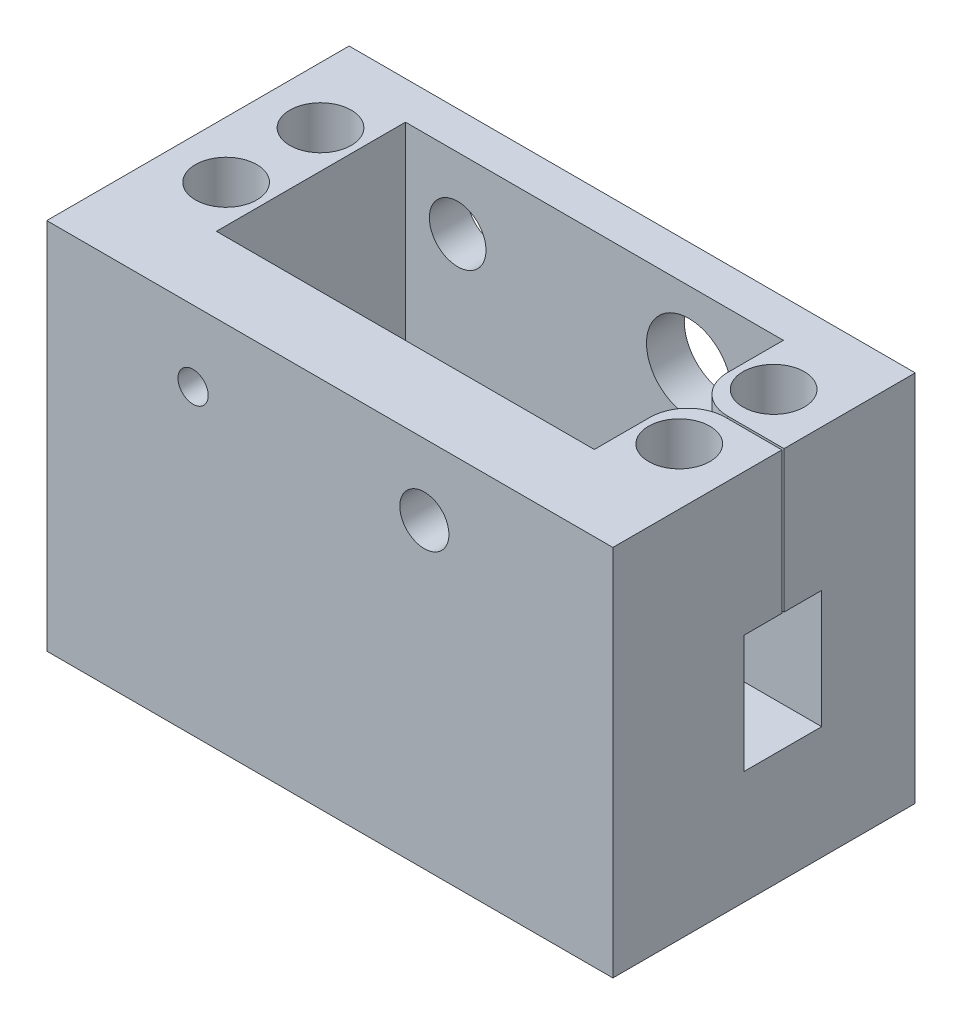
SolidWorks part; units mm, degrees
ref_plane "Front Plane" through (0, 0, 0) normal (0, 0, 1) x (1, 0, 0)
ref_plane "Top Plane" through (0, 0, 0) normal (0, 1, 0) x (1, 0, 0)
ref_plane "Right Plane" through (0, 0, 0) normal (1, 0, 0) x (0, 0, -1)
sketch "Sketch1" plane through (0, 0, 0) normal (0, 1, 0) x (1, 0, 0)
  line L0 (20.015, 0) -> (27.985, 0)
  line L1 (27.985, -14.015) -> (-27.985, -14.015)
  line L2 (27.985, -14.015) -> (27.985, 14.015)
  line L3 (27.985, 14.015) -> (-27.985, 14.015)
  line L4 (-27.985, -14.015) -> (-27.985, 14.015)
  line L5 (27.985, -14.015) -> (-27.985, 14.015) construction
  line L6 (27.985, 14.015) -> (-27.985, -14.015) construction
  line L7 (20.015, -10.015) -> (-20.015, -10.015)
  line L8 (20.015, -10.015) -> (20.015, 10.015)
  line L9 (20.015, 10.015) -> (-20.015, 10.015)
  line L10 (-20.015, -10.015) -> (-20.015, 10.015)
  line L11 (20.015, -10.015) -> (-20.015, 10.015) construction
  line L12 (20.015, 10.015) -> (-20.015, -10.015) construction
  line L13 (24, -5) -> (-24, -5) construction
  line L14 (24, -5) -> (24, 5) construction
  line L15 (24, 5) -> (-24, 5) construction
  line L16 (-24, -5) -> (-24, 5) construction
  line L17 (24, -5) -> (-24, 5) construction
  line L18 (24, 5) -> (-24, -5) construction
  line L19 (-27.985, -14.015) -> (-27.985, -18.015)
  line L20 (-27.985, -18.015) -> (27.985, -18.015)
  line L21 (27.985, -18.015) -> (27.985, -14.015)
  line L22 (27.985, 14.015) -> (29.985, 14.015)
  line L23 (29.985, 14.015) -> (29.985, 0.115)
  line L24 (29.985, 0.115) -> (24, 0.115)
  line L25 (27.985, -14.015) -> (29.985, -14.015)
  line L26 (29.985, -14.015) -> (29.985, -0.115)
  line L27 (29.985, -0.115) -> (24, -0.115)
  line L28 (27.985, -18.015) -> (29.985, -18.015)
  line L29 (29.985, -18.015) -> (29.985, -14.015)
  line L30 (-27.985, 14.015) -> (-29.985, 14.015)
  line L31 (-29.985, 14.015) -> (-29.985, -18.015)
  line L32 (-29.985, -18.015) -> (-27.985, -18.015)
  circle A1 centre (24, 5) radius 3.25
  circle A2 centre (24, -5) radius 3.25
  circle A3 centre (-24, -5) radius 3.25
  circle A4 centre (-24, 5) radius 3.25
  arc A5 (20.015, 4.1) -> (27.985, 4.1) centre (24, 4.1) ccw
  arc A6 (20.015, -4.1) -> (27.985, -4.1) centre (24, -4.1) cw
  point P0 (0, 0)
  point P6 (0, 0)
  point P11 (0, 0)
  dimension "D1" = 6.5
  dimension "D7" = 4.1
  dimension "D8" = 4.1
  dimension "D2" = 48
  dimension "D3" = 4
  dimension "D4" = 40.03
  dimension "D5" = 20.03
  dimension "D6" = 10
  dimension "D9" = 4
  dimension "D10" = 2
  dimension "D11" = 2
extrude "Boss-Extrude1" add sketch "Sketch1" along normal mid plane 15 contours A6 L8 L7 L10 L9 A5 L2 L3 L4 L1 A4 A3 A2 A1 | L20 L21 L1 L19 | L24 L23 L22 L2 | L26 L27 L2 L25 | L27 A6 L2 | A5 L24 L2 | L28 L29 L25 L21 | L31 L32 L19 L4 L30
sketch "Sketch2" plane through (0, -7.5, 0) normal (0, -1, 0) x (1, 0, 0)
  circle A0 centre (24, -5) radius 3.25 construction
  circle A1 centre (24, 5) radius 3.25 construction
  circle A2 centre (-24, -5) radius 3.25 construction
  circle A3 centre (-24, 5) radius 3.25 construction
  circle A4 centre (24, -5) radius 3.25
  circle A5 centre (24, 5) radius 3.25
  circle A6 centre (-24, -5) radius 3.25
  circle A7 centre (-24, 5) radius 3.25
extrude "Boss-Extrude2" add sketch "Sketch2" against normal offset from surface (5 mm away) 10 up to face at (10.4535, 7.5, 0.5714)
sketch "Sketch3" plane through (0, 0, 18.015) normal (0, 0, 1) x (1, 0, 0)
  line L0 (10.015, 0) -> (-10.485, 0) construction
  line L1 (-10.485, 0) -> (-14.485, 0) construction
  circle A2 centre (10.015, 0) radius 2.6
  circle A3 centre (-14.485, 0) radius 1.6
  dimension "D3" = 5.2
  dimension "D4" = 3.2
  dimension "D1" = 4
  dimension "D2" = 20.5
  dimension "D5" = 10
extrude "Cut-Extrude1" cut sketch "Sketch3" against normal blind 10 contours A3 | A2
sketch "Sketch4" plane through (0, 0, -14.015) normal (0, 0, -1) x (-1, 0, 0)
  line L4 (-29.985, -7.5) -> (29.985, -7.5)
  line L5 (29.985, -7.5) -> (29.985, 7.5)
  line L6 (29.985, 7.5) -> (-29.985, 7.5)
  line L7 (-29.985, 7.5) -> (-29.985, -7.5)
  line L8 (-29.985, -7.5) -> (29.985, -7.5)
  line L10 (29.985, 7.5) -> (-29.985, 7.5)
  line L12 (-29.985, 7.5) -> (-29.985, -7.5)
  line L13 (29.985, -7.5) -> (29.985, 7.5)
  circle A2 centre (-10.015, 0) radius 4.5
  circle A3 centre (14.485, 0) radius 1.6 construction
  circle A4 centre (14.485, 0) radius 1.6 construction
  circle A5 centre (14.485, 0) radius 3
  circle A6 centre (-10.015, 0) radius 2.6 construction
  circle A7 centre (-10.015, 0) radius 2.6 construction
  dimension "D2" = 9
  dimension "D3" = 6
  dimension "D1" = 0
extrude "Cut-Extrude2" cut sketch "Sketch4" against normal offset from surface (28.03 mm away) 4 contours A5 | A2 up to face at (-12.885, 0, 18.015)
sketch "Sketch5" plane through (0, -7.5, 0) normal (0, -1, 0) x (1, 0, 0)
  line L0 (20.015, -4.1) -> (29.985, -4.1)
  line L1 (20.015, 4.1) -> (29.985, 4.1)
  line L2 (0, 0) -> (-20.015, 0) construction
  line L12 (-29.985, 18.015) -> (-29.985, -14.015)
  line L13 (-29.985, -14.015) -> (29.985, -14.015)
  line L14 (29.985, -14.015) -> (29.985, -0.115)
  line L15 (29.985, -0.115) -> (24, -0.115)
  line L16 (20.015, -4.1) -> (20.015, -10.015)
  line L17 (20.015, -10.015) -> (-20.015, -10.015)
  line L18 (-20.015, -10.015) -> (-20.015, 10.015)
  line L19 (-20.015, 10.015) -> (20.015, 10.015)
  line L20 (20.015, 10.015) -> (20.015, 4.1)
  line L21 (24, 0.115) -> (29.985, 0.115)
  line L22 (29.985, 0.115) -> (29.985, 18.015)
  line L23 (29.985, 18.015) -> (-29.985, 18.015)
  line L24 (-29.985, 18.015) -> (-29.985, -14.015)
  line L25 (-29.985, -14.015) -> (29.985, -14.015)
  line L26 (29.985, -14.015) -> (29.985, -0.115)
  line L27 (29.985, -0.115) -> (24, -0.115)
  line L28 (20.015, -4.1) -> (20.015, -10.015)
  line L29 (20.015, -10.015) -> (-20.015, -10.015)
  line L30 (-20.015, -10.015) -> (-20.015, 10.015)
  line L31 (-20.015, 10.015) -> (20.015, 10.015)
  line L32 (20.015, 10.015) -> (20.015, 4.1)
  line L33 (24, 0.115) -> (29.985, 0.115)
  line L34 (29.985, 0.115) -> (29.985, 18.015)
  line L35 (29.985, 18.015) -> (-29.985, 18.015)
  arc A2 (24, -0.115) -> (20.015, -4.1) centre (24, -4.1) ccw
  arc A3 (20.015, 4.1) -> (24, 0.115) centre (24, 4.1) ccw
  arc A4 (24, -0.115) -> (20.015, -4.1) centre (24, -4.1) ccw
  arc A5 (20.015, 4.1) -> (24, 0.115) centre (24, 4.1) ccw
  point P17 (0, 0)
  line M18 (-29.985, 18.015) -> (-29.985, -14.015)
  line M19 (-29.985, -14.015) -> (29.985, -14.015)
  line M20 (29.985, -14.015) -> (29.985, -0.115)
  line M23 (20.015, -4.1) -> (20.015, -10.015)
  line M24 (20.015, -10.015) -> (-20.015, -10.015)
  line M25 (-20.015, -10.015) -> (-20.015, 10.015)
  line M26 (-20.015, 10.015) -> (20.015, 10.015)
  line M27 (20.015, 10.015) -> (20.015, 4.1)
  line M30 (29.985, 0.115) -> (29.985, 18.015)
  line M31 (29.985, 18.015) -> (-29.985, 18.015)
  dimension "D1" = 0
extrude "Boss-Extrude3" add sketch "Sketch5" along normal offset from surface (12.5 mm away) 27.5 contours L1 L0 L30 M27 M30 M31 M18 M19 M20 M23 M24 M25 M26 up to face at (10.4535, 7.5, 0.5714)
sketch "Sketch6" plane through (0, -20, 0) normal (0, -1, 0) x (1, 0, 0)
  line L1 (-29.985, -14.015) -> (29.985, -14.015)
  line L2 (-29.985, -14.015) -> (-29.985, 18.015)
  line L3 (-29.985, 18.015) -> (29.985, 18.015)
  line L4 (29.985, -14.015) -> (29.985, 18.015)
extrude "Boss-Extrude4" add sketch "Sketch6" along normal blind 12
